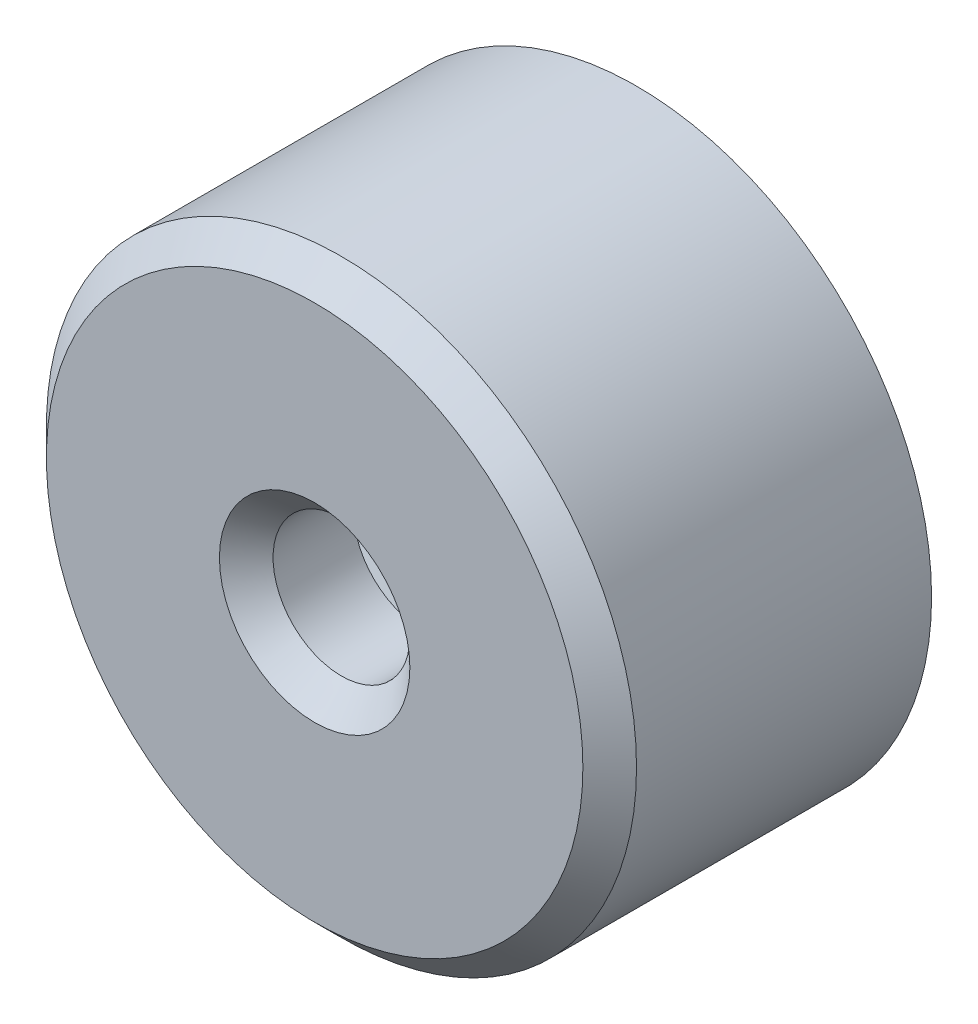
SolidWorks part; units mm, degrees
ref_plane "Front Plane" through (0, 0, 0) normal (0, 0, 1) x (1, 0, 0)
ref_plane "Top Plane" through (0, 0, 0) normal (0, 1, 0) x (1, 0, 0)
ref_plane "Right Plane" through (0, 0, 0) normal (1, 0, 0) x (0, 0, -1)
sketch "Sketch1" plane through (0, 0, 0) normal (0, 0, 1) x (1, 0, 0)
  line L0 (0, 0) -> (0, 39.0917) construction
  line L1 (4.05, 2.3383) -> (0, 4.6765)
  line L2 (0, 4.6765) -> (-4.05, 2.3383)
  line L3 (-4.05, 2.3383) -> (-4.05, -2.3383)
  line L4 (-4.05, -2.3383) -> (0, -4.6765)
  line L5 (0, -4.6765) -> (4.05, -2.3383)
  line L6 (4.05, -2.3383) -> (4.05, 2.3383)
  circle A0 centre (0, 0) radius 11
  circle A1 centre (0, 0) radius 4.05 construction
  dimension "D1" = 8.1
  dimension "D2" = 22
extrude "Boss-Extrude1" add sketch "Sketch1" along normal blind 8
sketch "Sketch2" plane through (0, 0, 8) normal (0, 0, 1) x (1, 0, 0)
  circle A0 centre (0, 0) radius 11
  circle A1 centre (0, 0) radius 2.55
  dimension "D1" = 22
  dimension "D2" = 5.1
extrude "Boss-Extrude2" add sketch "Sketch2" along normal blind 4
chamfer "Chamfer1" distance 1 angle 45 8 edges at (11, 0, 12) (-2.025, -3.5074, 0) (-4.05, 0, 0) (-2.025, 3.5074, 0) (2.025, 3.5074, 0) (4.05, 0, 0) (2.025, -3.5074, 0) (2.55, 0, 12)
